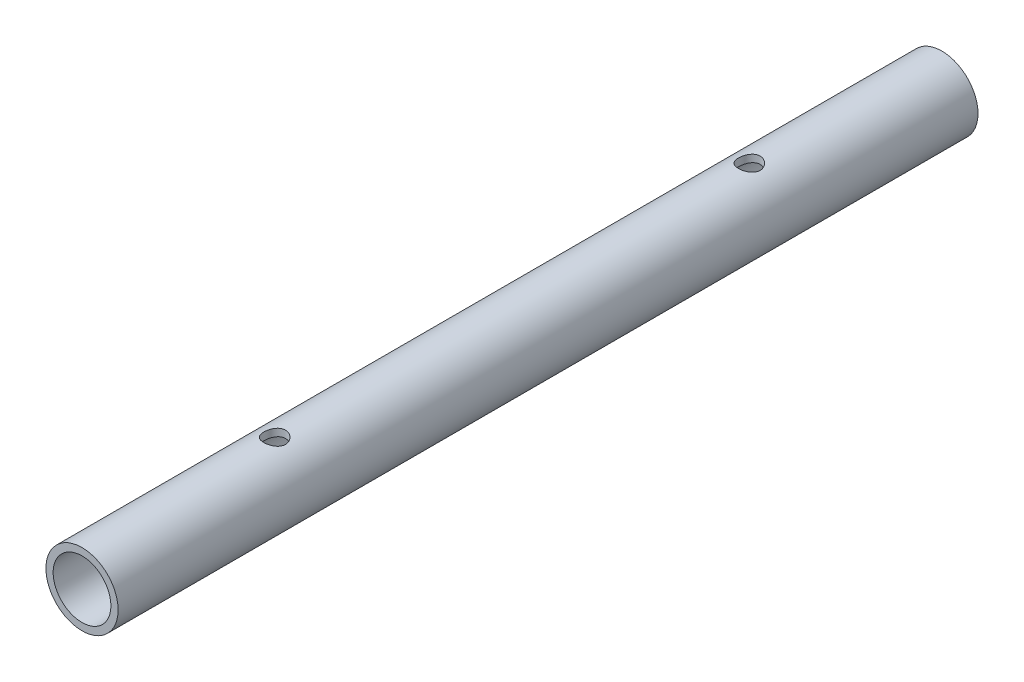
SolidWorks part; units mm, degrees
ref_plane "Plan de face" through (0, 0, 0) normal (0, 0, 1) x (1, 0, 0)
ref_plane "Plan de dessus" through (0, 0, 0) normal (0, 1, 0) x (1, 0, 0)
ref_plane "Plan de droite" through (0, 0, 0) normal (1, 0, 0) x (0, 0, -1)
sketch "Sketch1" plane through (0, 0, 0) normal (0, 0, 1) x (1, 0, 0)
  circle A0 centre (0, 0) radius 5
extrude "Boss-Extrude1" add sketch "Sketch1" along normal blind 119.147
sketch "Sketch2" plane through (0, 0, 119.147) normal (0, 0, 1) x (1, 0, 0)
  circle A0 centre (0, 0) radius 4
extrude "Cut-Extrude1" cut sketch "Sketch2" against normal up to next
sketch "Sketch5" plane through (0, 0, 0) normal (0, 1, 0) x (1, 0, 0)
  circle A0 centre (0, -26.689) radius 1.5
  circle A1 centre (0, -92.458) radius 1.5
  dimension "D1" = 26.689
  dimension "D2" = 92.458
extrude "Cut-Extrude2" cut sketch "Sketch5" against normal through all and the other way through all
